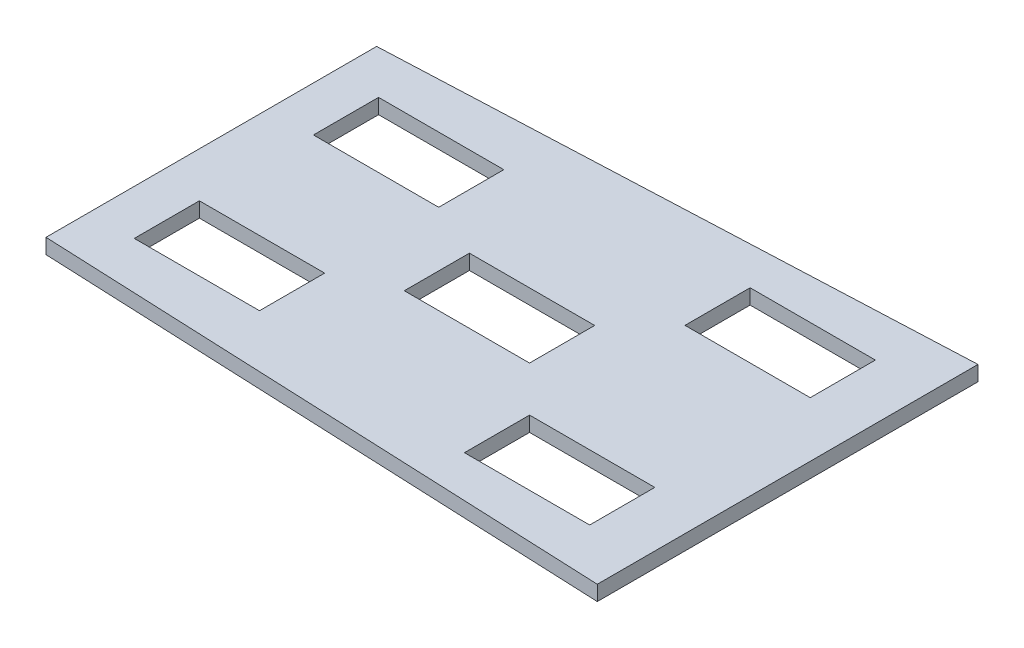
SolidWorks part; units mm, degrees
ref_plane "Front Plane" through (0, 0, 0) normal (0, 0, 1) x (1, 0, 0)
ref_plane "Top Plane" through (0, 0, 0) normal (0, 1, 0) x (1, 0, 0)
ref_plane "Right Plane" through (0, 0, 0) normal (1, 0, 0) x (0, 0, -1)
sketch "Sketch1" plane through (0, 0, 0) normal (0, 1, 0) x (1, 0, 0)
  line L0 (-57.5, -0.0237) -> (57.5, 0.0237) construction
  line L1 (-57.5, -33.0237) -> (57.5, -37.9763)
  line L2 (-57.5, -33.0237) -> (-57.5, 32.9763)
  line L3 (-57.5, 32.9763) -> (57.5, 38.0237)
  line L4 (57.5, -37.9763) -> (57.5, 38.0237)
  line L5 (0, -35.5) -> (0, 35.5) construction
  point P0 (0, 0)
  point P8 (0, 0)
  dimension "D1" = 115
  dimension "D2" = 76
  dimension "D3" = 66
  dimension "D4" = 115
extrude "Boss-Extrude1" add sketch "Sketch1" along normal blind 3
sketch "Sketch2" plane through (0, 3, 0) normal (0, 1, 0) x (1, 0, 0)
  line L0 (0, 35.2652) -> (0, -35.8599) construction
  line L1 (21.5, -15.4943) -> (46.5, -15.4943)
  line L2 (21.5, -15.4943) -> (21.5, -28.4943)
  line L3 (21.5, -28.4943) -> (46.5, -28.4943)
  line L4 (46.5, -15.4943) -> (46.5, -28.4943)
  line L5 (21.5, -15.4943) -> (46.5, -28.4943) construction
  line L6 (21.5, -28.4943) -> (46.5, -15.4943) construction
  line L7 (-12.5, 6.5) -> (12.5, 6.5)
  line L8 (-12.5, 6.5) -> (-12.5, -6.5)
  line L9 (-12.5, -6.5) -> (12.5, -6.5)
  line L10 (12.5, 6.5) -> (12.5, -6.5)
  line L11 (-12.5, 6.5) -> (12.5, -6.5) construction
  line L12 (-12.5, -6.5) -> (12.5, 6.5) construction
  line L13 (-48.5, -11.4029) -> (-23.5, -11.4029)
  line L14 (-48.5, -11.4029) -> (-48.5, -24.4029)
  line L15 (-48.5, -24.4029) -> (-23.5, -24.4029)
  line L16 (-23.5, -11.4029) -> (-23.5, -24.4029)
  line L17 (-48.5, -11.4029) -> (-23.5, -24.4029) construction
  line L18 (-48.5, -24.4029) -> (-23.5, -11.4029) construction
  line L20 (-48.5, 11.3627) -> (-23.5, 11.3627)
  line L21 (-48.5, 11.3627) -> (-48.5, 24.3627)
  line L22 (-48.5, 24.3627) -> (-23.5, 24.3627)
  line L23 (-23.5, 11.3627) -> (-23.5, 24.3627)
  line L24 (-48.5, 11.3627) -> (-23.5, 24.3627) construction
  line L25 (-48.5, 24.3627) -> (-23.5, 11.3627) construction
  line L26 (21.5, 15.5322) -> (46.5, 15.5322)
  line L27 (21.5, 15.5322) -> (21.5, 28.5322)
  line L28 (21.5, 28.5322) -> (46.5, 28.5322)
  line L29 (46.5, 15.5322) -> (46.5, 28.5322)
  line L30 (21.5, 15.5322) -> (46.5, 28.5322) construction
  line L31 (21.5, 28.5322) -> (46.5, 15.5322) construction
  line L33 (-57.5, 32.9763) -> (-57.5, -33.0237) construction
  line L34 (-57.5, -33.0237) -> (57.5, -37.9763) construction
  line L35 (57.5, 38.0237) -> (-57.5, 32.9763) construction
  point P0 (34, -21.9943)
  point P5 (0, 0)
  point P10 (-36, -17.9029)
  point P18 (34, 22.0322)
  point P19 (-36, 17.8627)
  dimension "D1" = 25
  dimension "D2" = 13
  dimension "D3" = 25
  dimension "D4" = 13
  dimension "D5" = 25
  dimension "D6" = 13
  dimension "D7" = 25
  dimension "D8" = 13
  dimension "D9" = 25
  dimension "D10" = 13
  dimension "D11" = 9
  dimension "D12" = 9
  dimension "D13" = 9
  dimension "D14" = 9
  dimension "D15" = 9
  dimension "D16" = 9
  dimension "D17" = 9
  dimension "D18" = 9
extrude "Cut-Extrude1" cut sketch "Sketch2" against normal blind 3
